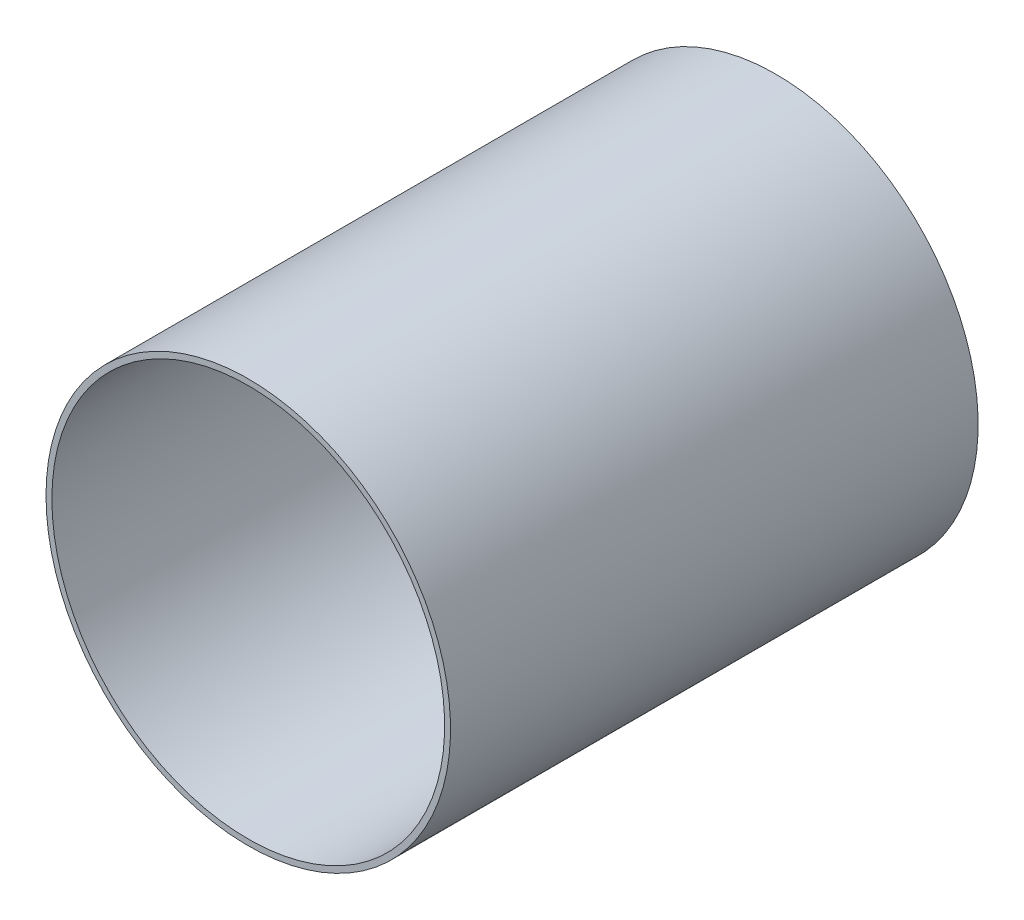
SolidWorks part; units mm, degrees
ref_plane "Ön Düzlem" through (0, 0, 0) normal (0, 0, 1) x (1, 0, 0)
ref_plane "Üst Düzlem" through (0, 0, 0) normal (0, 1, 0) x (1, 0, 0)
ref_plane "Sağ Düzlem" through (0, 0, 0) normal (1, 0, 0) x (0, 0, -1)
sketch "Çizim1" plane through (0, 0, 0) normal (0, 0, 1) x (1, 0, 0)
  circle A0 centre (0, 0) radius 34.5
  circle A2 centre (0, 0) radius 33.5
extrude "Yükseklik-Ekstrüzyon2" add sketch "Çizim1" along normal blind 90 contours A0 | A2
